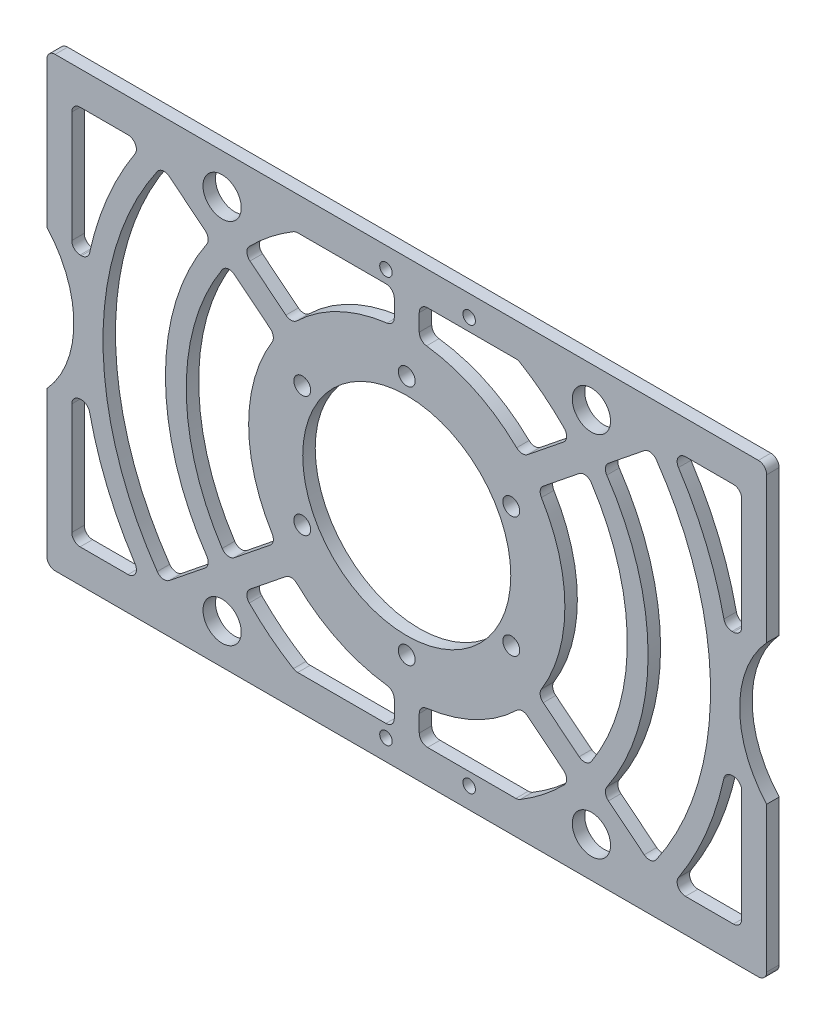
SolidWorks part; units mm, degrees
material "Thornel Mat VMA"
ref_plane "前视基准面" through (0, 0, 0) normal (0, 0, 1) x (1, 0, 0)
ref_plane "上视基准面" through (0, 0, 0) normal (0, 1, 0) x (1, 0, 0)
ref_plane "右视基准面" through (0, 0, 0) normal (1, 0, 0) x (0, 0, -1)
sketch "草图1" plane through (0, 0, 0) normal (0, 0, 1) x (1, 0, 0)
  line L1 (-142, -53.75) -> (142, -53.75)
  line L2 (-142, -53.75) -> (-142, 53.75)
  line L3 (-142, 53.75) -> (142, 53.75)
  line L4 (142, -53.75) -> (142, 53.75)
  line L5 (0, 53.75) -> (0, -53.75) construction
  line L6 (-142, 0) -> (142, 0) construction
  point P0 (0, 0)
  dimension "D1" = 107.5
  dimension "D2" = 284
extrude "凸台-拉伸1" add sketch "草图1" along normal mid plane 3
sketch "草图2" plane through (0, 0, 1.5) normal (0, 0, 1) x (1, 0, 0)
  line L0 (142, 53.75) -> (-142, 53.75) construction
  line L1 (-86.5, -53.75) -> (86.5, -53.75) construction
  line L2 (-86.5, -53.75) -> (-86.5, 53.75) construction
  line L3 (-86.5, 53.75) -> (86.5, 53.75) construction
  line L4 (86.5, -53.75) -> (86.5, 53.75) construction
  line L5 (0, 53.75) -> (0, -53.75) construction
  line L6 (-86.5, 0) -> (86.5, 0) construction
  line L7 (-142, 53.75) -> (-86.5, 53.75)
  line L8 (-142, 53.75) -> (-142, -53.75) construction
  line L9 (-142, 53.75) -> (-142, -53.75)
  line L10 (-142, -53.75) -> (-86.5, -53.75)
  line L11 (86.5, 53.75) -> (142, 53.75)
  line L12 (142, -53.75) -> (142, 53.75) construction
  line L13 (142, 53.75) -> (142, -53.75)
  line L14 (142, -53.75) -> (86.5, -53.75)
  line L15 (86.5, 53.75) -> (86.5, -53.75)
  line L16 (-86.5, 53.75) -> (-86.5, -53.75)
  point P0 (0, 0)
  dimension "D1" = 173
extrude "切除-拉伸1" cut sketch "草图2" against normal blind 10
sketch "草图4" plane through (0, 0, 1.5) normal (0, 0, 1) x (1, 0, 0)
  circle A0 centre (0, 0) radius 29 construction
  circle A1 centre (0, 29) radius 2.025
  circle A2 centre (25.1147, 14.5) radius 2.025
  circle A3 centre (25.1147, -14.5) radius 2.025
  circle A4 centre (0, -29) radius 2.025
  circle A5 centre (-25.1147, -14.5) radius 2.025
  circle A6 centre (-25.1147, 14.5) radius 2.025
  circle A7 centre (0, 0) radius 25
  point P17 (0, 0)
  dimension "D1" = 58
  dimension "D2" = 4.05
  dimension "D4" = 4
  dimension "D3" = 6
extrude "切除-拉伸2" cut sketch "草图4" against normal blind 10
fillet "圆角1" radius 2 4 edges at (86.5, 53.75, 0) (86.5, -53.75, 0) (-86.5, -53.75, 0) (-86.5, 53.75, 0)
sketch "草图5" plane through (0, 0, 1.5) normal (0, 0, 1) x (1, 0, 0)
  line L0 (-105, 0) -> (0, 0) construction
  circle A0 centre (-105, 0) radius 25
  dimension "D2" = 50
  dimension "D1" = 105
extrude "切除-拉伸3" cut sketch "草图5" against normal blind 10
mirror "镜向1" about plane through (0, 0, 0) normal (1, 0, 0) of "切除-拉伸3"
sketch "草图6" plane through (0, 0, 1.5) normal (0, 0, 1) x (1, 0, 0)
  line L0 (0, 45.75) -> (0, -45.75) construction
  line L1 (-56.8853, 45.75) -> (56.8853, 45.75)
  line L2 (84.5, 53.75) -> (-84.5, 53.75) construction
  line L3 (-56.8853, -45.75) -> (56.8853, -45.75)
  line L4 (-84.5, -53.75) -> (84.5, -53.75) construction
  line L5 (56.8853, 45.75) -> (-56.8853, -45.75) construction
  line L6 (-56.8853, 45.75) -> (56.8853, -45.75) construction
  line L7 (-3, 45.75) -> (-3, -45.75)
  line L8 (55.0052, 48.0878) -> (-58.7654, -43.4122)
  line L9 (-58.7654, 43.4122) -> (55.0052, -48.0878)
  line L10 (3, 45.75) -> (3, -45.75)
  line L11 (58.7654, 43.4122) -> (-55.0052, -48.0878)
  line L12 (-55.0052, 48.0878) -> (58.7654, -43.4122)
  circle A0 centre (0, 0) radius 33 construction
  circle A1 centre (0, 0) radius 25 construction
  circle A2 centre (0, 0) radius 38
  arc A3 (26.757, -45.75) -> (26.757, 45.75) centre (0, 0) ccw
  arc A4 (35.6502, -45.75) -> (35.6502, 45.75) centre (0, 0) ccw
  arc A5 (56.8853, -45.75) -> (56.8853, 45.75) centre (0, 0) ccw
  circle A6 centre (0, 0) radius 73 construction
  circle A7 centre (0, 0) radius 58 construction
  circle A8 centre (0, 0) radius 53 construction
  arc A9 (-56.8853, 45.75) -> (-56.8853, -45.75) centre (0, 0) ccw
  arc A10 (-35.6502, 45.75) -> (-35.6502, -45.75) centre (0, 0) ccw
  arc A11 (-26.757, 45.75) -> (-26.757, -45.75) centre (0, 0) ccw
  dimension "D1" = 8
  dimension "D6" = 8
  dimension "D7" = 8
  dimension "D2" = 5
  dimension "D3" = 15
  dimension "D4" = 5
  dimension "D5" = 15
  dimension "D8" = 3
  dimension "D9" = 3
extrude "切除-拉伸4" cut sketch "草图6" against normal blind 10 contours A10 L9 A9 L8 | L9 A11 L8 A2 | L1 A11 L12 A2 L7 | L8 A3 L1 L10 A2 | L12 A3 L11 A2 | L3 A3 L9 A2 L10 | L11 A11 L3 L7 A2 | L12 A5 L11 A4
sketch "草图7" plane through (0, 0, 1.5) normal (0, 0, 1) x (1, 0, 0)
  line L2 (-84.5, -53.75) -> (84.5, -53.75) construction
  line L4 (47.0162, -33.9629) -> (58.7174, -43.3736) construction
  line L5 (0, 0) -> (0, -53.75) construction
  line L6 (0, 0) -> (109.6235, 0) construction
  circle A0 centre (44.3727, -44.1528) radius 4.5972
  arc A4 (26.757, -45.75) -> (39.3539, -35.5003) centre (0, 0) ccw construction
  circle A5 centre (-44.3727, -44.1528) radius 4.5972
  circle A6 centre (-44.3727, 44.1528) radius 4.5972
  circle A7 centre (44.3727, 44.1528) radius 4.5972
  dimension "D1" = 5
  dimension "D2" = 5
  dimension "D3" = 5
extrude "切除-拉伸5" cut sketch "草图7" against normal blind 10
sketch "草图8" plane through (0, 0, 1.5) normal (0, 0, 1) x (1, 0, 0)
  line L0 (-80.5, 45.75) -> (-80.5, 15)
  line L1 (-80.5, 15) -> (-76.5441, 15)
  line L2 (-86.5, 16.8152) -> (-86.5, 51.75) construction
  line L3 (-63.1739, 45.75) -> (-80.5, 45.75)
  line L4 (-26.757, 45.75) -> (-3, 45.75) construction
  line L5 (59.2321, 50.75) -> (-59.2321, 50.75)
  line L6 (-59.2321, -50.75) -> (59.2321, -50.75)
  arc A0 (-86.5, -16.8152) -> (-86.5, 16.8152) centre (-105, 0) ccw construction
  arc A4 (59.2321, -50.75) -> (59.2321, 50.75) centre (0, 0) ccw
  arc A5 (-59.2321, 50.75) -> (-59.2321, -50.75) centre (0, 0) ccw
  arc A7 (-63.1739, 45.75) -> (-76.5441, 15) centre (0, 0) ccw
  dimension "D2" = 6
  dimension "D3" = 15
  dimension "D1" = 5
extrude "切除-拉伸6" cut sketch "草图8" against normal blind 10
mirror "镜向2" about plane through (0, 0, 0) normal (1, 0, 0) of "切除-拉伸6"
mirror "镜向3" about plane through (0, 0, 0) normal (0, 1, 0) of "镜向2", "切除-拉伸6"
fillet "圆角2" radius 2 52 edges at (-80.5, -15, 0) (-76.5441, -15, 0) (80.5, 15, 0) (76.5441, 15, 0) (63.1739, 45.75, 0) (80.5, 45.75, 0) (-3, 37.8814, 0) (-3, -37.8814, 0) (-27.639, 26.0785, 0) (31.3992, -21.403, 0) (-39.3539, 35.5003, 0) (-26.757, 45.75, 0) (-3, 45.75, 0) (-31.3992, -21.403, 0) (27.639, 26.0785, 0) (-43.1142, -30.8247, 0) (-43.1142, 30.8247, 0) (-31.3992, 21.403, 0) (27.639, -26.0785, 0) (3, 37.8814, 0) (3, -37.8814, 0) (3, 45.75, 0) (26.757, 45.75, 0) (39.3539, 35.5003, 0) (-58.7174, -43.3736, 0) (-58.7174, 43.3736, 0) (-47.0162, 33.9629, 0) (-47.0162, -33.9629, 0) (47.0162, -33.9629, 0) (47.0162, 33.9629, 0) (58.7174, 43.3736, 0) (58.7174, -43.3736, 0) (31.3992, 21.403, 0) (-27.639, -26.0785, 0) (-3, -45.75, 0) (-26.757, -45.75, 0) (-39.3539, -35.5003, 0) (3, -45.75, 0) (39.3539, -35.5003, 0) (26.757, -45.75, 0) (43.1142, 30.8247, 0) (43.1142, -30.8247, 0) (-63.1739, 45.75, 0) (-76.5441, 15, 0) (-80.5, 15, 0) (-80.5, 45.75, 0) (63.1739, -45.75, 0) (76.5441, -15, 0) (80.5, -15, 0) (80.5, -45.75, 0) (-80.5, -45.75, 0) (-63.1739, -45.75, 0)
sketch "草图10" plane through (0, 0, 1.5) normal (0, 0, 1) x (1, 0, 0)
  line L0 (0, 0) -> (38, 0) construction
  circle A0 centre (-5, 48.75) radius 1.25 construction
  circle A1 centre (15, 48.75) radius 1.25 construction
  circle A2 centre (-5, 48.75) radius 1.25 construction
  circle A3 centre (15, 48.75) radius 1.25 construction
  circle A4 centre (-5, 48.75) radius 1.5
  circle A5 centre (15, 48.75) radius 1.5
  arc A6 (32.3562, -19.9268) -> (32.3562, 19.9268) centre (0, 0) ccw construction
  circle A7 centre (15, -48.75) radius 1.25 construction
  circle A8 centre (-5, -48.75) radius 1.25 construction
  circle A9 centre (15, -48.75) radius 1.5
  circle A10 centre (-5, -48.75) radius 1.5
  dimension "D1" = 3
extrude "切除-拉伸7" cut sketch "草图10" against normal blind 10
equation "\"D7@草图6\"=\"D6@草图6\""
